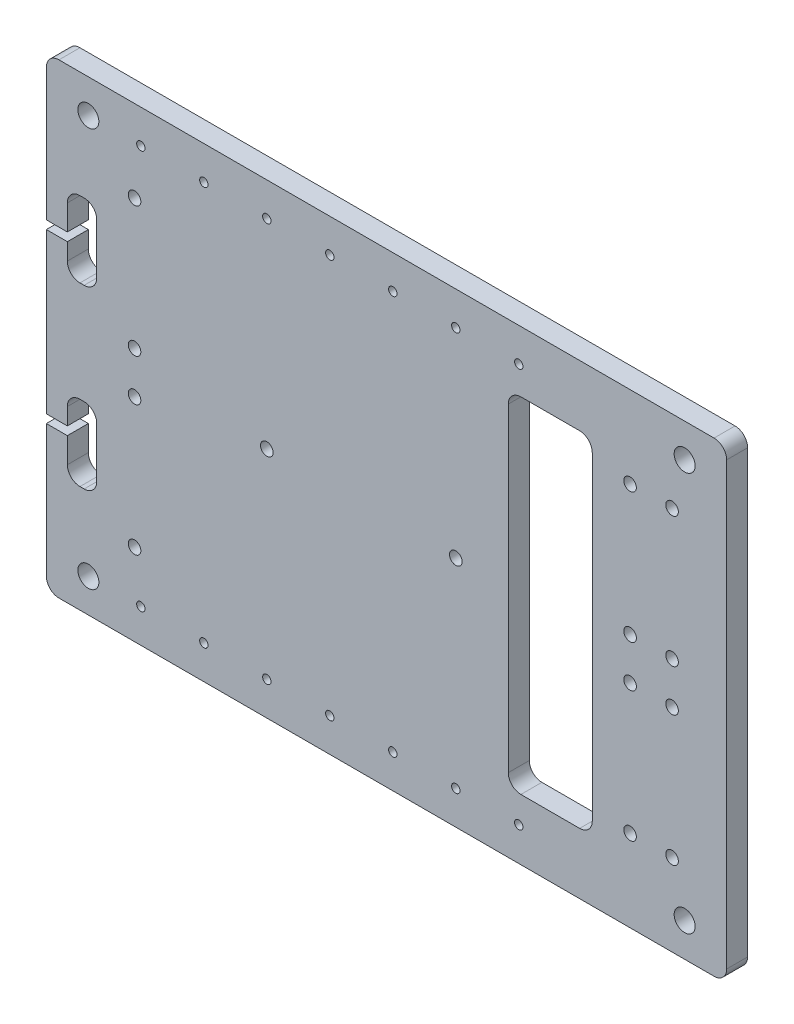
SolidWorks part; units mm, degrees
ref_plane "前视基准面" through (0, 0, 0) normal (0, 0, 1) x (1, 0, 0)
ref_plane "上视基准面" through (0, 0, 0) normal (0, 1, 0) x (1, 0, 0)
ref_plane "右视基准面" through (0, 0, 0) normal (1, 0, 0) x (0, 0, -1)
sketch "草图1" plane through (0, 0, 0) normal (0, 0, 1) x (1, 0, 0)
  line L1 (0, 0) -> (162, 0)
  line L2 (0, 0) -> (0, -111)
  line L3 (0, -111) -> (162, -111)
  line L4 (162, 0) -> (162, -111)
  dimension "D1" = 111
  dimension "D2" = 162
extrude "凸台-拉伸1" add sketch "草图1" along normal blind 5
sketch "草图2" plane through (0, 0, 0) normal (0, 0, -1) x (-1, 0, 0)
  line L8 (-130, -96.5) -> (-130, -14.5)
  line L9 (-130, -14.5) -> (-110, -14.5)
  line L10 (-110, -14.5) -> (-110, -96.5)
  line L11 (-110, -96.5) -> (-130, -96.5)
extrude "切除-拉伸1" cut sketch "草图2" against normal up to next
sketch "草图3" plane through (0, 0, 5) normal (0, 0, 1) x (1, 0, 0)
  line L0 (162, -55.5) -> (0, -55.5) construction
  line L1 (162, -111) -> (162, 0) construction
  line L2 (0, 0) -> (0, -111) construction
  line L3 (162, 0) -> (0, 0) construction
  line L7 (5, -85.5) -> (5, -25.5)
  line L8 (5, -25.5) -> (12, -25.5)
  line L9 (12, -25.5) -> (12, -85.5)
  line L13 (5, -85.5) -> (12, -85.5)
  line L15 (0, 0) -> (0, -111) construction
  circle A0 centre (149, -60.5) radius 1.5
  circle A1 centre (139, -60.5) radius 1.5
  circle A2 centre (149, -91.5) radius 1.5
  circle A3 centre (139, -91.5) radius 1.5
  circle A4 centre (149, -50.5) radius 1.5
  circle A5 centre (139, -50.5) radius 1.5
  circle A20 centre (22.5, -103) radius 1
  circle A27 centre (22.5, -8) radius 1
  circle A34 centre (21, -60.5) radius 1.5
  circle A35 centre (21, -91.5) radius 1.5
  circle A36 centre (21, -50.5) radius 1.5
  circle A37 centre (21, -19.5) radius 1.5
  circle A43 centre (10, -8) radius 2.5
  circle A44 centre (152, -8) radius 2.5
  circle A45 centre (152, -103) radius 2.5
  circle A46 centre (10, -103) radius 2.5
  circle A47 centre (37.5, -103) radius 1
  circle A48 centre (52.5, -103) radius 1
  circle A49 centre (67.5, -103) radius 1
  circle A50 centre (82.5, -103) radius 1
  circle A51 centre (97.5, -103) radius 1
  circle A52 centre (37.5, -8) radius 1
  circle A53 centre (52.5, -8) radius 1
  circle A54 centre (67.5, -8) radius 1
  circle A55 centre (82.5, -8) radius 1
  circle A56 centre (97.5, -8) radius 1
  circle A57 centre (112.5, -8) radius 1
  circle A58 centre (139, -19.5) radius 1.5
  circle A59 centre (149, -19.5) radius 1.5
  circle A60 centre (112.5, -103) radius 1
  circle A61 centre (52.5, -55.5) radius 1.5
  circle A62 centre (97.5, -55.5) radius 1.5
  point P113 (12, -55.5)
  point P114 (5, -55.5)
  dimension "D1" = 3
  dimension "D7" = 22.5
  dimension "D12" = 3
  dimension "D20" = 5
  dimension "D25" = 5
  dimension "D29" = 22.5
  dimension "D5" = 10
  dimension "D6" = 7
  dimension "D8" = 7
  dimension "D2" = 5
  dimension "D3" = 5
  dimension "D4" = 10
  dimension "D21" = 10
  dimension "D22" = 8
  dimension "D23" = 8
  dimension "D26" = 5
  dimension "D27" = 7
  dimension "D28" = 30
extrude "切除-拉伸2" cut sketch "草图3" against normal up to next (5 mm away)
fillet "圆角1" radius 3 12 edges at (162, -111, 2.5) (162, 0, 2.5) (0, 0, 2.5) (0, -111, 2.5) (12, -85.5, 2.5) (5, -85.5, 2.5) (12, -25.5, 2.5) (5, -25.5, 2.5) (110, -96.5, 2.5) (130, -96.5, 2.5) (110, -14.5, 2.5) (130, -14.5, 2.5)
sketch "草图4" plane through (0, 0, 0) normal (-1, 0, 0) x (0, 0, 1)
  line L0 (0, -55.5) -> (5, -55.5) construction
  line L1 (0, -3) -> (0, -108) construction
  line L2 (5, -82.5) -> (5, -28.5) construction
  circle A0 centre (2.5, -35.5) radius 1
  circle A1 centre (2.5, -75.5) radius 1
  dimension "D2" = 2
  dimension "D1" = 20
  dimension "D3" = 2.5
extrude "切除-拉伸3" cut sketch "草图4" against normal up to next
sketch "Sketch2" plane through (0, 0, 0) normal (0, 0, 1) x (1, 0, 0)
  line L0 (0, -55.5) -> (5, -55.5) construction
  line L1 (0, -3) -> (0, -108) construction
  line L2 (5, -28.5) -> (5, -82.5) construction
  line L3 (5, -67.5) -> (5, -43.5)
  line L4 (5, -43.5) -> (12, -43.5)
  line L5 (12, -82.5) -> (12, -28.5) construction
  line L6 (12, -43.5) -> (12, -67.5)
  line L7 (5, -67.5) -> (12, -67.5)
  point P12 (12, -55.5)
  dimension "D1" = 24
extrude "Boss-Extrude2" add sketch "Sketch2" along normal blind 5
sketch "Sketch3" plane through (0, 0, 5) normal (0, 0, 1) x (1, 0, 0)
  line L0 (0, -55.5) -> (5, -55.5) construction
  line L1 (0, -3) -> (0, -108) construction
  line L2 (5, -55.5) -> (5, -43.5) construction
  line L3 (2.5, -55.5) -> (2.5, -35.5) construction
  line L4 (5, -28.5) -> (5, -43.5) construction
  line L5 (0, -34.5) -> (5, -34.5)
  line L6 (0, -34.5) -> (0, -36.5)
  line L7 (0, -36.5) -> (5, -36.5)
  line L8 (5, -34.5) -> (5, -36.5)
  line L9 (0, -34.5) -> (5, -36.5) construction
  line L10 (0, -36.5) -> (5, -34.5) construction
  line L11 (5, -76.5) -> (5, -74.5)
  line L12 (0, -74.5) -> (5, -74.5)
  line L13 (0, -76.5) -> (0, -74.5)
  line L14 (0, -76.5) -> (5, -76.5)
  dimension "D1" = 2
  dimension "D2" = 20
extrude "Cut-Extrude1" cut sketch "Sketch3" against normal through all
fillet "Fillet1" radius 3 4 edges at (12, -67.5, 2.5) (5, -67.5, 2.5) (12, -43.5, 2.5) (5, -43.5, 2.5)
